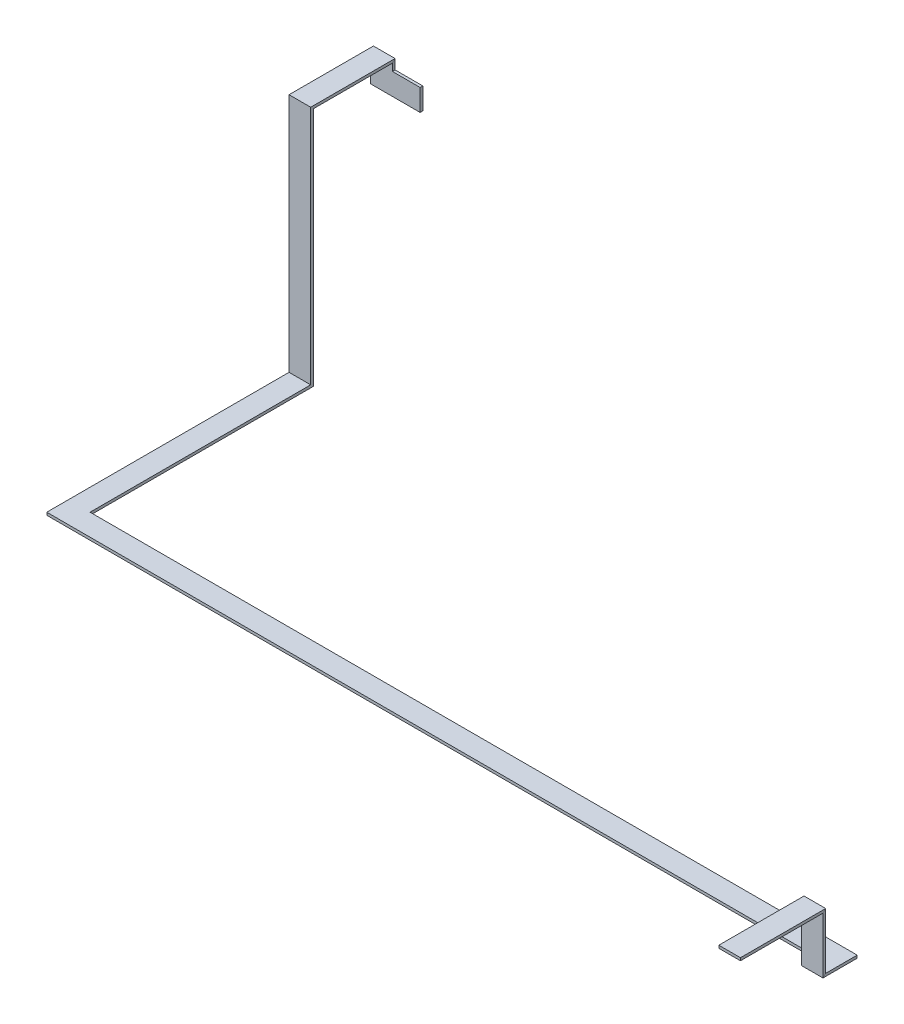
SolidWorks part; units mm, degrees
ref_plane "Alzado" through (0, 0, 0) normal (0, 0, 1) x (1, 0, 0)
ref_plane "Planta" through (0, 0, 0) normal (0, 1, 0) x (1, 0, 0)
ref_plane "Vista lateral" through (0, 0, 0) normal (1, 0, 0) x (0, 0, -1)
sketch "Croquis2" plane through (0, 0, 0) normal (0, 0, 1) x (1, 0, 0)
  line L1 (-25.4, 285.195) -> (25.4, 285.195)
  line L2 (-25.4, 285.195) -> (-25.4, -285.195)
  line L3 (-25.4, -285.195) -> (25.4, -285.195)
  line L4 (25.4, 285.195) -> (25.4, -285.195)
  line L5 (-25.4, 285.195) -> (25.4, -285.195) construction
  line L6 (-25.4, -285.195) -> (25.4, 285.195) construction
  point P0 (0, 0)
  dimension "D1" = 570.39
  dimension "D2" = 50.8
extrude "Saliente-Extruir1" add sketch "Croquis2" along normal blind 6.31
sketch "Croquis3" plane through (0, 0, 6.31) normal (0, 0, 1) x (1, 0, 0)
  line L1 (-25.4, -278.885) -> (25.4, -278.885)
  line L2 (-25.4, -278.885) -> (-25.4, -285.195)
  line L3 (-25.4, -285.195) -> (25.4, -285.195)
  line L4 (25.4, -278.885) -> (25.4, -285.195)
  line L5 (-25.4, -278.885) -> (25.4, -285.195) construction
  line L6 (-25.4, -285.195) -> (25.4, -278.885) construction
  point P0 (0, -282.04)
  dimension "D1" = 6.31
  dimension "D2" = 50.8
extrude "Saliente-Extruir2" add sketch "Croquis3" along normal blind 568.44
sketch "Croquis4" plane through (25.4, 0, 0) normal (1, 0, 0) x (0, 0, -1)
  line L1 (-523.95, -285.195) -> (-574.75, -285.195)
  line L2 (-523.95, -285.195) -> (-523.95, -278.885)
  line L3 (-523.95, -278.885) -> (-574.75, -278.885)
  line L4 (-574.75, -285.195) -> (-574.75, -278.885)
  line L5 (-523.95, -285.195) -> (-574.75, -278.885) construction
  line L6 (-523.95, -278.885) -> (-574.75, -285.195) construction
  point P0 (-549.35, -282.04)
  dimension "D1" = 50.8
extrude "Saliente-Extruir3" add sketch "Croquis4" along normal blind 1800
sketch "Croquis6" plane through (0, 0, 0) normal (0, 0, -1) x (-1, 0, 0)
  line L1 (-25.4, 278.885) -> (25.4, 278.885)
  line L2 (-25.4, 278.885) -> (-25.4, 285.195)
  line L3 (-25.4, 285.195) -> (25.4, 285.195)
  line L4 (25.4, 278.885) -> (25.4, 285.195)
  line L5 (-25.4, 278.885) -> (25.4, 285.195) construction
  line L6 (-25.4, 285.195) -> (25.4, 278.885) construction
  point P0 (0, 282.04)
  dimension "D1" = 6.31
  dimension "D2" = 50.8
sketch3d "Croquis3D2"
  line L0 (0, 282.04, 0) -> (0, 282.04, -188.52)
  line L1 (0, 282.04, -188.52) -> (0, 211.24, -188.52)
  dimension "D1" = 188.52
  dimension "D2" = 70.8
sweep "Barrer1" add profiles "Croquis6" path "Croquis3D2"
sketch "Croquis7" plane through (0, 0, -191.675) normal (0, 0, -1) x (-1, 0, 0)
  line L0 (-25.4, 211.24) -> (-85.4, 211.24)
  line L1 (-85.4, 211.24) -> (-85.4, 285.195)
  line L2 (-85.4, 285.195) -> (-25.4, 285.195)
  line L3 (-25.4, 285.195) -> (-25.4, 211.24)
  dimension "D1" = 60
sketch "Croquis9" plane through (0, 0, 574.75) normal (0, 0, 1) x (1, 0, 0)
  line L0 (1825.4, -278.885) -> (-25.4, -278.885) construction
  line L1 (1774.6, -278.885) -> (1825.4, -278.885)
  line L2 (1774.6, -278.885) -> (1774.6, -285.195)
  line L3 (1774.6, -285.195) -> (1825.4, -285.195)
  line L4 (1825.4, -278.885) -> (1825.4, -285.195)
  line L5 (1774.6, -278.885) -> (1825.4, -285.195) construction
  line L6 (1774.6, -285.195) -> (1825.4, -278.885) construction
  point P0 (1800, -282.04)
  dimension "D1" = 50.8
sketch3d "Croquis3D3"
  line L0 (1800, -282.04, 574.75) -> (1800, -282.04, 601.16)
  line L1 (1800, -282.04, 601.16) -> (1800, -150.28, 601.16)
  line L2 (1800, -150.28, 601.16) -> (1800, -150.28, 797.94)
  dimension "D1" = 26.41
  dimension "D2" = 131.76
  dimension "D3" = 196.78
sweep "Barrer2" add profiles "Croquis9" path "Croquis3D3"
sketch "Croquis10" plane through (25.4, 0, 0) normal (1, 0, 0) x (0, 0, -1)
  line L0 (191.675, 211.24) -> (185.365, 211.24)
  line L1 (185.365, 211.24) -> (185.365, 262.04)
  line L2 (185.365, 278.885) -> (185.365, 211.24) construction
  line L3 (185.365, 262.04) -> (191.675, 262.04)
  line L4 (191.675, 262.04) -> (191.675, 211.24)
  dimension "D1" = 50.8
extrude "Saliente-Extruir4" add sketch "Croquis10" along normal blind 65
